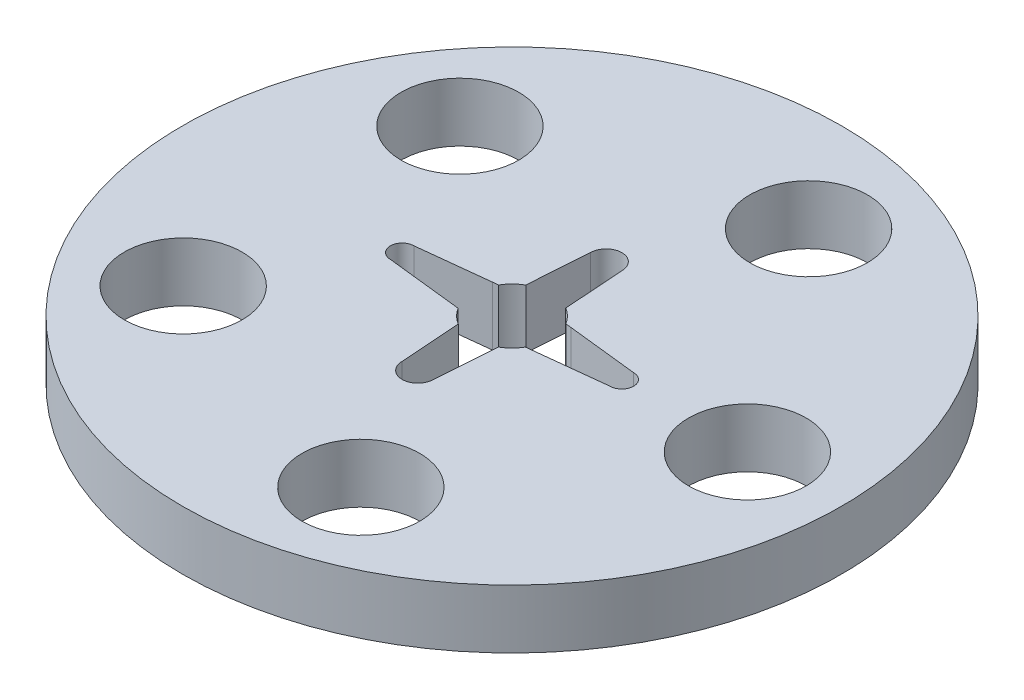
SolidWorks part; units mm, degrees
ref_plane "Front Plane" through (0, 0, 0) normal (0, 0, 1) x (1, 0, 0)
ref_plane "Top Plane" through (0, 0, 0) normal (0, 1, 0) x (1, 0, 0)
ref_plane "Right Plane" through (0, 0, 0) normal (1, 0, 0) x (0, 0, -1)
sketch "Sketch1" plane through (0, 0, 0) normal (0, 1, 0) x (1, 0, 0)
  line L0 (0, -12) -> (0, 12) construction
  line L1 (-14, 0) -> (14, 0) construction
  line L2 (-4.9997, -2.4973) -> (-4.9997, 2.4973) construction
  line L3 (-2.497, 5) -> (2.4976, 5) construction
  line L4 (5.0003, 2.4972) -> (5.0003, -2.4973) construction
  line L5 (4.9997, -2.4973) -> (4.2852, -2.5757)
  line L6 (-14, 1.5) -> (-4.9997, 2.4973)
  line L7 (-4.9997, 2.4973) -> (-4.2852, 2.5757)
  line L9 (-14, -1.5) -> (-4.9997, -2.4973)
  line L10 (-4.9997, -2.4973) -> (-4.2852, -2.5757)
  line L11 (-2, -12) -> (-2.497, -5)
  line L12 (-2.497, -5) -> (-2.5465, -4.3026)
  line L13 (2, -12) -> (2.4975, -5)
  line L14 (2.4975, -5) -> (2.5466, -4.3025)
  line L15 (14, -1.5) -> (4.9997, -2.4973)
  line L16 (2.4975, -5) -> (0, -5) construction
  line L17 (4.9997, 2.4973) -> (4.2852, 2.5757)
  line L18 (14, 1.5) -> (4.9997, 2.4973)
  line L19 (2.4975, 5) -> (2.5466, 4.3025)
  line L20 (2, 12) -> (2.4975, 5)
  line L21 (-2.497, 5) -> (-2.5465, 4.3026)
  line L22 (-2, 12) -> (-2.497, 5)
  circle A0 centre (30, 0) radius 7.5
  circle A1 centre (9.2705, -28.5317) radius 7.5
  circle A2 centre (-24.2705, -17.6336) radius 7.5
  circle A3 centre (-24.2705, 17.6336) radius 7.5
  circle A4 centre (9.2705, 28.5317) radius 7.5
  circle A5 centre (0, 0) radius 42
  arc A12 (-4.2852, -2.5757) -> (-2.5465, -4.3026) centre (0, 0) ccw
  arc A13 (-14, 1.5) -> (-14, -1.5) centre (-14, 0) ccw
  arc A14 (2, 12) -> (-2, 12) centre (0, 12) ccw
  arc A15 (2, -12) -> (-2, -12) centre (0, -12) cw
  arc A16 (14, 1.5) -> (14, -1.5) centre (14, 0) cw
  arc A17 (2.5466, -4.3025) -> (4.2852, -2.5757) centre (0, 0) ccw
  arc A20 (-2.5465, 4.3026) -> (-4.2852, 2.5757) centre (0, 0) ccw
  arc A21 (4.2852, 2.5757) -> (2.5466, 4.3025) centre (0, 0) ccw
  point P25 (-4.9997, 0)
  point P34 (0.0003, 0)
  dimension "D1" = 15
  dimension "D4" = 4
  dimension "D2" = 30
  dimension "D3" = 5
extrude "Boss-Extrude2" add sketch "Sketch1" along normal blind 7.5
